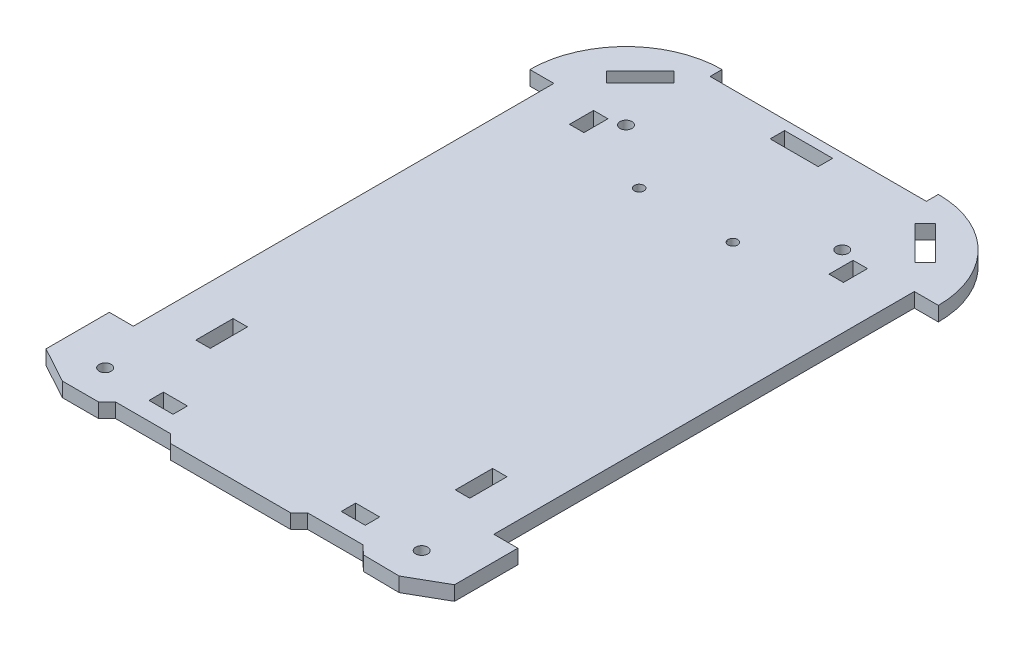
SolidWorks part; units mm, degrees
ref_plane "Front Plane" through (0, 0, 0) normal (0, 0, 1) x (1, 0, 0)
ref_plane "Top Plane" through (0, 0, 0) normal (0, 1, 0) x (1, 0, 0)
ref_plane "Right Plane" through (0, 0, 0) normal (1, 0, 0) x (0, 0, -1)
sketch "Sketch1" plane through (0, 0, 0) normal (0, 1, 0) x (1, 0, 0)
  line L0 (-45, 125.0784) -> (-45, 120.0784)
  line L2 (-85, -116.2613) -> (-85, -89.9216)
  line L4 (85, -116.2613) -> (85, -89.9216)
  line L5 (-79.9711, -124.9048) -> (79.9711, 124.9048) construction
  line L6 (-80.0287, 124.652) -> (80.3131, -125.0949) construction
  line L7 (-45, 120.0784) -> (45, 120.0784)
  line L8 (45, 120.0784) -> (45, 125.0784)
  line L9 (-85, 85.0784) -> (-75, 85.0784)
  line L10 (-75, 85.0784) -> (-75, -89.9216)
  line L11 (-75, -89.9216) -> (-85, -89.9216)
  line L12 (85, 85.0784) -> (75, 85.0784)
  line L13 (75, 85.0784) -> (75, -89.9216)
  line L14 (75, -89.9216) -> (85, -89.9216)
  line L15 (-85, -116.2613) -> (-69.9815, -124.4502)
  line L16 (70.3232, -124.6447) -> (85, -116.2613)
  line L43 (50.5716, 109.8107) -> (54.8142, 114.0533)
  line L44 (50.5716, 109.8107) -> (64.7137, 95.6685)
  line L45 (54.8142, 114.0533) -> (68.9564, 99.9112)
  line L46 (64.7137, 95.6685) -> (68.9564, 99.9112)
  line L47 (10, 110.0784) -> (10, 116.0784)
  line L48 (-50.1104, 110.2719) -> (-64.2525, 96.1297)
  line L49 (-50.1104, 110.2719) -> (-54.353, 114.5145)
  line L50 (-54.353, 114.5145) -> (-68.4952, 100.3724)
  line L51 (-64.2525, 96.1297) -> (-68.4952, 100.3724)
  line L52 (-69.9815, -124.4502) -> (-54.9815, -124.4502)
  line L54 (-54.9815, -124.4502) -> (-51.4459, -120.9147)
  line L55 (-51.4459, -120.9147) -> (-28.5212, -120.9147)
  line L57 (-24.9857, -124.4502) -> (25.0143, -124.4502)
  line L62 (-19.5, 65.0784) -> (19.5, 65.0784) construction
  line L63 (-10, 116.0784) -> (-10, 110.0784)
  line L64 (-10, 110.0784) -> (10, 110.0784)
  line L65 (-10, 116.0784) -> (10, 116.0784)
  line L86 (-28.5212, -120.9147) -> (-24.9857, -124.4502)
  line L89 (0.0143, -124.4502) -> (0.0143, -110.0155) construction
  line L90 (28.5499, -120.9147) -> (25.0143, -124.4502)
  line L91 (51.4746, -120.9147) -> (28.5499, -120.9147)
  line L92 (55.3232, -124.4502) -> (51.4746, -120.9147)
  line L93 (70.3232, -124.6447) -> (55.3232, -124.4502)
  line L94 (55.3232, -124.4502) -> (-54.9815, -124.4502) construction
  line L95 (75, -89.9216) -> (75, -81.9216) construction
  line L96 (-39.9836, -120.9147) -> (-39.9836, -110.9147) construction
  line L97 (40.0122, -120.9147) -> (40.0122, -110.9147) construction
  line L98 (-34.9836, -107.4147) -> (-34.9836, -113.4147)
  line L99 (-44.9836, -113.4147) -> (-34.9836, -113.4147)
  line L100 (-44.9836, -107.4147) -> (-34.9836, -107.4147)
  line L101 (-44.9836, -107.4147) -> (-44.9836, -113.4147)
  line L102 (45.0122, -107.4147) -> (35.0122, -107.4147)
  line L103 (35.0122, -107.4147) -> (35.0122, -113.4147)
  line L104 (45.0122, -113.4147) -> (35.0122, -113.4147)
  line L105 (45.0122, -107.4147) -> (45.0122, -113.4147)
  line L106 (75, -81.9216) -> (57, -81.9216) construction
  line L107 (0, 0) -> (0, -82.551) construction
  line L108 (57, -81.9216) -> (57, -66.4216)
  line L109 (57, -66.4216) -> (51, -66.4216)
  line L110 (51, -66.4216) -> (51, -81.9216)
  line L111 (51, -81.9216) -> (57, -81.9216)
  line L112 (-51, -66.4216) -> (-51, -81.9216)
  line L113 (-57, -66.4216) -> (-51, -66.4216)
  line L114 (-57, -81.9216) -> (-57, -66.4216)
  line L115 (-51, -81.9216) -> (-57, -81.9216)
  line L116 (57, -66.4216) -> (57, 73.5784) construction
  line L117 (57, 73.5784) -> (51, 73.5784)
  line L118 (51, 73.5784) -> (51, 83.5784)
  line L119 (51, 83.5784) -> (57, 83.5784)
  line L120 (57, 83.5784) -> (57, 73.5784)
  line L121 (-51, -66.4216) -> (-51, 73.5784) construction
  line L122 (-51, 73.5784) -> (-51, 83.5784)
  line L123 (-51, 83.5784) -> (-57, 83.5784)
  line L124 (-57, 83.5784) -> (-57, 73.5784)
  line L125 (-57, 73.5784) -> (-51, 73.5784)
  arc A0 (-85, 85.0784) -> (-45, 125.0784) centre (-45, 85.0784) cw
  arc A1 (45, 125.0784) -> (85, 85.0784) centre (45, 85.0784) cw
  circle A9 centre (-45, 85.0784) radius 2.5
  circle A10 centre (45, 85.0784) radius 2.5
  circle A17 centre (-65.8579, -110.7794) radius 2.5
  circle A18 centre (65.8579, -110.7794) radius 2.5
  circle A19 centre (19.5, 65.0784) radius 2
  circle A20 centre (-19.5, 65.0784) radius 2
  point P0 (0, 0)
  point P41 (-39.9836, -110.9147)
  point P71 (0, 112.5784)
  point P76 (0, 65.0784)
  dimension "D3" = 40
  dimension "D4" = 40
  dimension "D10" = 10
  dimension "D11" = 5
  dimension "D15" = 79.9958
  dimension "D16" = 6
  dimension "D17" = 39
  dimension "D18" = 5
  dimension "D21" = 90
  dimension "D22" = 15
  dimension "D19" = 55
  dimension "D20" = 170
  dimension "D14" = 10
  dimension "D27" = 5
  dimension "D28" = 4
  dimension "D29" = 4
  dimension "D1" = 160
  dimension "D2" = 250
  dimension "D5" = 5
  dimension "D6" = 10
  dimension "D7" = 10
  dimension "D8" = 175
  dimension "D9" = 175
  dimension "D23" = 50
  dimension "D24" = 15
  dimension "D25" = 6
  dimension "D26" = 46.0977
  dimension "D30" = 6
  dimension "D31" = 6
  dimension "D32" = 20
  dimension "D33" = 20
  dimension "D34" = 6
  dimension "D35" = 8
  dimension "D36" = 18
  dimension "D37" = 15.5
  dimension "D38" = 6
  dimension "D39" = 140
  dimension "D40" = 10
  dimension "D41" = 6
  dimension "D42" = 140
  dimension "D43" = 10
  dimension "D44" = 6
  dimension "D45" = 18
extrude "Boss-Extrude1" add sketch "Sketch1" along normal blind 6
